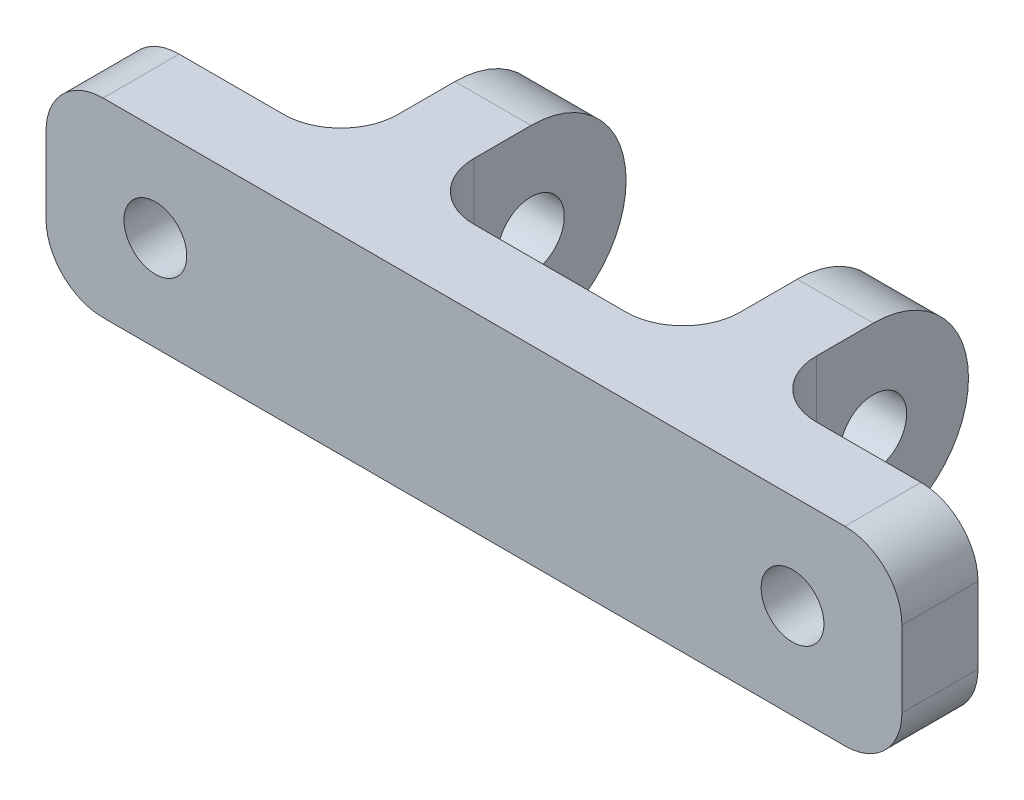
SolidWorks part; units mm, degrees
ref_plane "Front Plane" through (0, 0, 0) normal (0, 0, 1) x (1, 0, 0)
ref_plane "Top Plane" through (0, 0, 0) normal (0, 1, 0) x (1, 0, 0)
ref_plane "Right Plane" through (0, 0, 0) normal (1, 0, 0) x (0, 0, -1)
sketch "Sketch1" plane through (0, 0, 0) normal (0, 1, 0) x (1, 0, 0)
  line L0 (0, 0) -> (0, -7.5) construction
  line L1 (22.5, -7.5) -> (-22.5, -7.5)
  line L2 (22.5, -7.5) -> (22.5, 7.5)
  line L3 (22.5, 7.5) -> (-22.5, 7.5)
  line L4 (-22.5, -7.5) -> (-22.5, 7.5)
  line L5 (22.5, -7.5) -> (-22.5, 7.5) construction
  line L6 (22.5, 7.5) -> (-22.5, -7.5) construction
  line L7 (-11, -3.5) -> (-22.5, -3.5)
  line L8 (-11, -3.5) -> (-11, 7.5)
  line L9 (-11, 7.5) -> (-22.5, 7.5)
  line L10 (-22.5, -3.5) -> (-22.5, 7.5)
  line L11 (-11, -3.5) -> (-22.5, 7.5) construction
  line L12 (-11, 7.5) -> (-22.5, -3.5) construction
  line L13 (7, -3.5) -> (-7, -3.5)
  line L14 (7, -3.5) -> (7, 7.5)
  line L15 (7, 7.5) -> (-7, 7.5)
  line L16 (-7, -3.5) -> (-7, 7.5)
  line L17 (7, -3.5) -> (-7, 7.5) construction
  line L18 (7, 7.5) -> (-7, -3.5) construction
  line L19 (11, 7.5) -> (22.5, 7.5)
  line L20 (22.5, -3.5) -> (22.5, 7.5)
  line L21 (11, -3.5) -> (22.5, -3.5)
  line L22 (11, -3.5) -> (11, 7.5)
  point P0 (0, 0)
  point P6 (-16.75, 2)
  point P7 (0, 2)
  dimension "D1" = 4
  dimension "D2" = 4
  dimension "D3" = 15
  dimension "D4" = 45
  dimension "D5" = 14
extrude "Boss-Extrude1" add sketch "Sketch1" along normal blind 10 contours L21 L22 L3 L14 L13 L16 L8 L7 L4 L1 L2
sketch "Sketch2" plane through (-11, 0, 0) normal (-1, 0, 0) x (0, 0, 1)
  line L0 (3.5, 10) -> (-7.5, 10) construction
  line L1 (3.5, 0) -> (-7.5, 0) construction
  line L4 (-7.5, 10) -> (-7.5, 0) construction
  line L5 (-2.5, 0) -> (-7.5, 0)
  line L6 (-7.5, 0) -> (-7.5, 10)
  line L7 (-7.5, 10) -> (-2.5, 10)
  arc A0 (-2.5, 10) -> (-2.5, 0) centre (-2.5, 5) ccw
  circle A1 centre (-2.5, 5) radius 1.75
  line M2 (-7.5, 0) -> (3.5, 0)
  line M4 (3.5, 10) -> (-7.5, 10)
  line M5 (-7.5, 10) -> (-7.5, 0)
  dimension "D1" = 3.5
extrude "Cut-Extrude1" cut sketch "Sketch2" against normal through all both and the other way through all contours A0 M4 M5 | A0 L6 M2 | A1
sketch "Sketch3" plane through (0, 0, 3.5) normal (0, 0, -1) x (-1, 0, 0)
  line L0 (22.5, 0) -> (11, 10) construction
  line L1 (0, 0) -> (0, 10) construction
  line L2 (-7, 0) -> (7, 0) construction
  line L3 (-7, 10) -> (7, 10) construction
  circle A0 centre (16.75, 5) radius 1.65
  circle A1 centre (-16.75, 5) radius 1.65
  dimension "D1" = 3.3
extrude "Cut-Extrude2" cut sketch "Sketch3" against normal through all
fillet "Fillet1" radius 3 8 edges at (-22.5, 0, 5.5) (-22.5, 10, 5.5) (22.5, 0, 5.5) (22.5, 10, 5.5) (11, 5, 3.5) (-11, 5, 3.5) (7, 5, 3.5) (-7, 5, 3.5)
